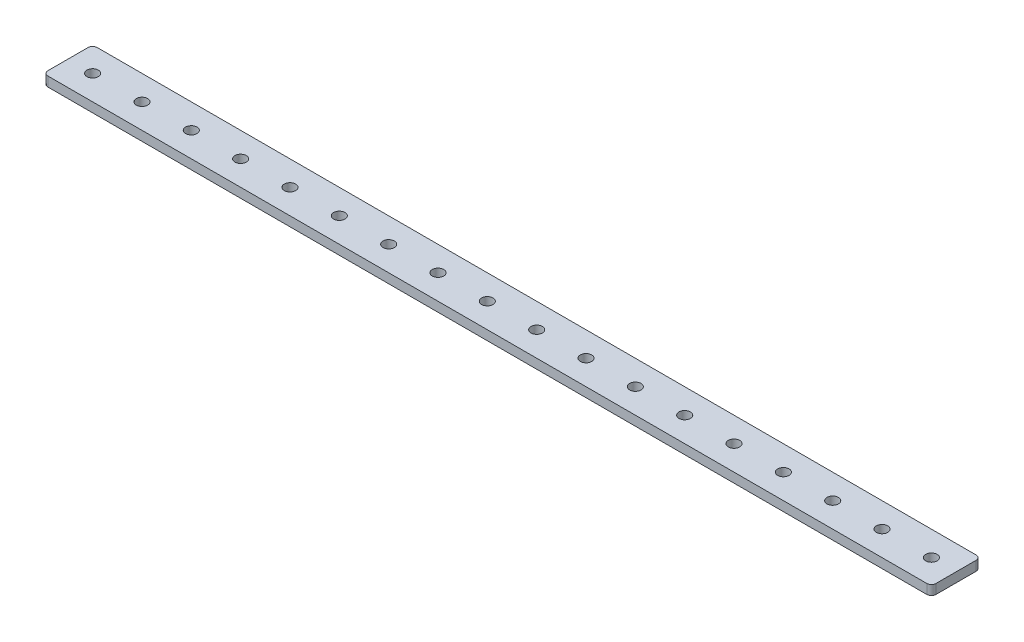
SolidWorks part; units mm, degrees
other "Defeature"
material "5052 Alloy"
ref_plane "Front Plane" through (0, 0, 0) normal (0, 0, 1) x (1, 0, 0)
ref_plane "Top Plane" through (0, 0, 0) normal (0, 1, 0) x (1, 0, 0)
ref_plane "Right Plane" through (0, 0, 0) normal (1, 0, 0) x (0, 0, -1)
sketch "Sketch1" plane through (0, 0, 0) normal (0, 1, 0) x (1, 0, 0)
  line L1 (-144, -8) -> (144, -8)
  line L2 (-144, -8) -> (-144, 8)
  line L3 (-144, 8) -> (144, 8)
  line L4 (144, -8) -> (144, 8)
  point P5 (0, 8)
  point P7 (144, 0)
  dimension "D1" = 288
  dimension "D2" = 16
extrude "Boss-Extrude1" add sketch "Sketch1" along normal blind 3.1
sketch "Sketch2" plane through (0, 3.1, 0) normal (0, 1, 0) x (1, 0, 0)
  line L0 (-144, 8) -> (-144, -8) construction
  circle A0 centre (-136, 0) radius 1.85
  circle A1 centre (-120, 0) radius 1.85
  circle A2 centre (-104, 0) radius 1.85
  circle A3 centre (-88, 0) radius 1.85
  circle A4 centre (-72, 0) radius 1.85
  circle A5 centre (-56, 0) radius 1.85
  circle A6 centre (-40, 0) radius 1.85
  circle A7 centre (-24, 0) radius 1.85
  circle A8 centre (-8, 0) radius 1.85
  circle A9 centre (8, 0) radius 1.85
  circle A10 centre (24, 0) radius 1.85
  circle A11 centre (40, 0) radius 1.85
  circle A12 centre (56, 0) radius 1.85
  circle A13 centre (72, 0) radius 1.85
  circle A14 centre (88, 0) radius 1.85
  circle A15 centre (104, 0) radius 1.85
  circle A16 centre (120, 0) radius 1.85
  circle A17 centre (136, 0) radius 1.85
  point P4 (-144, 0)
  dimension "D1" = 3.7
  dimension "D2" = 8
  dimension "D4" = 18
  dimension "D5" = 16
extrude "Cut-Extrude1" cut sketch "Sketch2" against normal through all
fillet "Fillet1" radius 1.5 4 edges at (144, 1.55, 8) (-144, 1.55, 8) (-144, 1.55, -8) (144, 1.55, -8)
